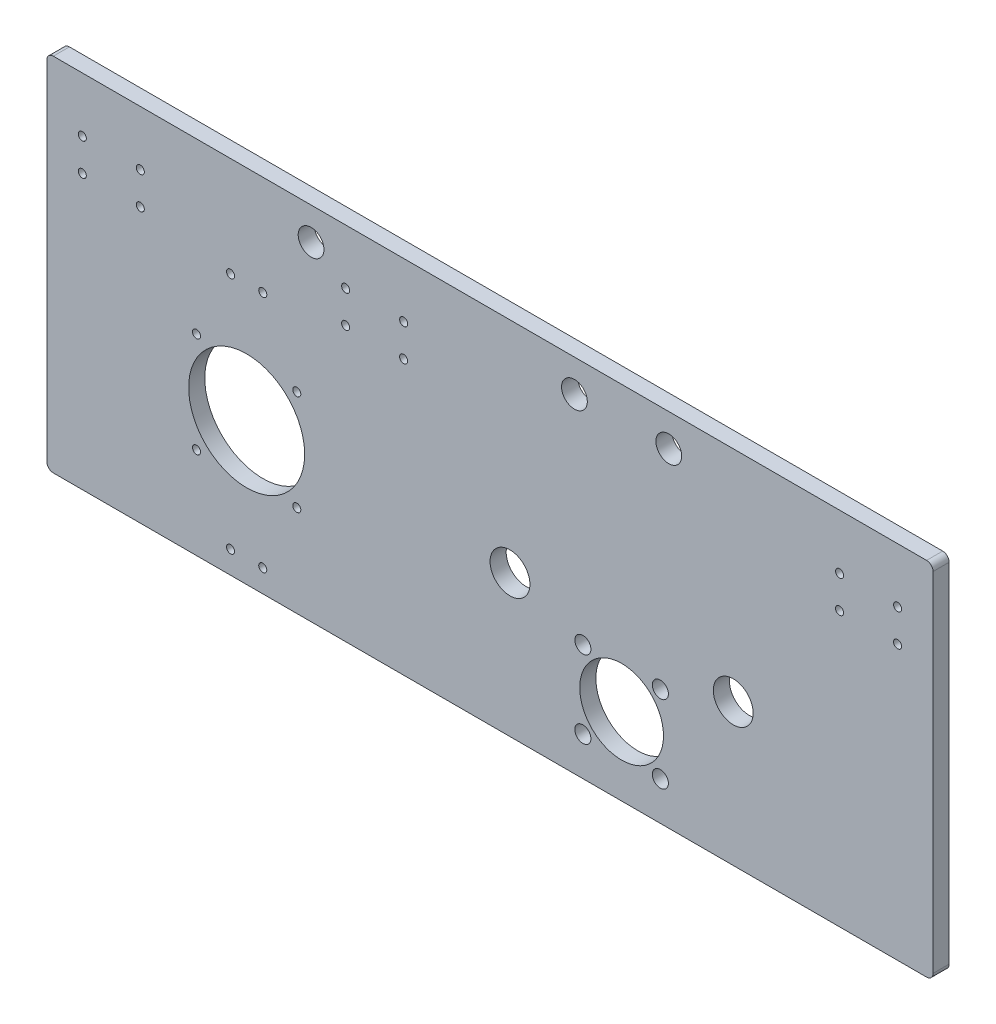
SolidWorks part; units mm, degrees
ref_plane "Спереди" through (0, 0, 0) normal (0, 0, 1) x (1, 0, 0)
ref_plane "Сверху" through (0, 0, 0) normal (0, 1, 0) x (1, 0, 0)
ref_plane "Справа" through (0, 0, 0) normal (1, 0, 0) x (0, 0, -1)
sketch "Эскиз1" plane through (0, 0, 0) normal (0, 0, 1) x (1, 0, 0)
  line L0 (-12.0208, 12.0208) -> (0, 0) construction
  line L1 (-178.359, 88) -> (96.641, 88)
  line L2 (-178.359, 88) -> (-178.359, -24)
  line L3 (-178.359, -24) -> (96.641, -24)
  line L4 (96.641, 88) -> (96.641, -24)
  line L5 (0, 0) -> (0, 88) construction
  line L6 (-34.641, 20) -> (0, 0) construction
  circle A0 centre (0, 0) radius 13
  circle A1 centre (-12.0208, 12.0208) radius 2.5
  circle A2 centre (12.0208, 12.0208) radius 2.5
  circle A3 centre (12.0208, -12.0208) radius 2.5
  circle A4 centre (-12.0208, -12.0208) radius 2.5
  circle A5 centre (-34.641, 20) radius 6.1833
  circle A6 centre (34.641, 20) radius 6.1833
  circle A7 centre (-116.359, 20) radius 18
  circle A8 centre (-14.641, 78) radius 4
  circle A9 centre (14.641, 78) radius 4
  circle A10 centre (-96.359, 78) radius 4
  circle A11 centre (-116.359, 20) radius 18 construction
  point P19 (0, 0)
  dimension "D2" = 5
  dimension "D4" = 26
  dimension "D9" = 8
  dimension "D1" = 45
  dimension "D3" = 17
  dimension "D6" = 58
  dimension "D7" = 20
  dimension "D8" = 20
  dimension "D10" = 10
  dimension "D12" = 40
  dimension "D13" = 20
  dimension "D14" = 275
  dimension "D15" = 82
  dimension "D16" = 82
  dimension "D11" = 112
  dimension "D5" = 4
extrude "Бобышка-Вытянуть1" add sketch "Эскиз1" along normal blind 5
hole_wizard "Отверстие обработанное метчиком M32" positions "Эскиз2" profile "Эскиз4" tap size "M3" standard "ISO" end condition through all
sketch "Эскиз2" plane through (0, 0, 0) normal (0, 0, -1) x (-1, 0, 0)
  point P0 (111.359, 57)
  point P3 (121.359, 57)
  point P6 (111.359, -17)
  point P9 (121.359, -17)
sketch "Эскиз4" plane through (-111.359, 57, 0) normal (1, 0, 0) x (0, 1, 0)
  line L0 (0, 0) -> (0, 5)
  line L1 (0, 5) -> (1.25, 5)
  line L2 (1.25, 5) -> (1.25, 0)
  line L5 (1.25, 0) -> (0, 0)
  line L11 (0, -6.35) -> (0, 107.95) construction
  dimension "Диаметр проходного сверла" = 2.5
  dimension "Глубина проходного сверла" = 5
cosmetic thread "Отверстие резьбы1" parameters "D2"=3
cosmetic thread "Отверстие резьбы2" parameters "D2"=3
cosmetic thread "Отверстие резьбы3" parameters "D2"=3
cosmetic thread "Отверстие резьбы4" parameters "D2"=3
hole_wizard "Отверстие обработанное метчиком M31" positions "Трехмерный эскиз1" profile "Эскиз6" tap size "M3" standard "ISO"
sketch3d "Трехмерный эскиз1"
  line L0 (-167.359, 71, 5) -> (-167.359, 71, 6) construction
  line L1 (-167.359, 61, 5) -> (-167.359, 61, 6) construction
  line L2 (-149.359, 61, 5) -> (-149.359, 61, 6) construction
  line L3 (-149.359, 71, 5) -> (-149.359, 71, 6) construction
  line L4 (-85.641, 71, 5) -> (-85.641, 71, 6) construction
  line L5 (-85.641, 61, 5) -> (-85.641, 61, 6) construction
  line L6 (-67.641, 61, 5) -> (-67.641, 61, 6) construction
  line L7 (-67.641, 71, 5) -> (-67.641, 71, 6) construction
  line L8 (67.641, 71, 5) -> (67.641, 71, 6) construction
  line L9 (67.641, 61, 5) -> (67.641, 61, 6) construction
  line L10 (85.641, 71, 5) -> (85.641, 71, 6) construction
  line L11 (85.641, 61, 5) -> (85.641, 61, 6) construction
  point P0 (-167.359, 71, 6)
  point P4 (-167.359, 61, 6)
  point P8 (-149.359, 61, 6)
  point P12 (-149.359, 71, 6)
  point P16 (-85.641, 71, 6)
  point P20 (-85.641, 61, 6)
  point P24 (-67.641, 61, 6)
  point P28 (-67.641, 71, 6)
  point P32 (67.641, 71, 6)
  point P36 (67.641, 61, 6)
  point P40 (85.641, 71, 6)
  point P44 (85.641, 61, 6)
sketch "Эскиз6" plane through (-167.359, 71, 6) normal (1, 0, 0) x (0, -1, 0)
  line L0 (0, 0) -> (0, 6.7501)
  line L1 (0, 6.7501) -> (1.25, 5.999)
  line L2 (1.25, 5.999) -> (1.25, 0)
  line L5 (1.25, 0) -> (0, 0)
  line L10 (0, 6.7501) -> (-1.25, 5.999) construction
  line L11 (0, -6.35) -> (0, 107.95) construction
  dimension "Диаметр сверла" = 2.5
  dimension "Глубина сверла" = 5.999
  dimension "Угол заточки сверла" = 118
cosmetic thread "Отверстие резьбы5" parameters "D1"=5, "D2"=3
cosmetic thread "Отверстие резьбы6" parameters "D1"=5, "D2"=3
cosmetic thread "Отверстие резьбы7" parameters "D1"=5, "D2"=3
cosmetic thread "Отверстие резьбы8" parameters "D1"=5, "D2"=3
cosmetic thread "Отверстие резьбы9" parameters "D1"=5, "D2"=3
cosmetic thread "Отверстие резьбы10" parameters "D1"=5, "D2"=3
cosmetic thread "Отверстие резьбы11" parameters "D1"=5, "D2"=3
cosmetic thread "Отверстие резьбы12" parameters "D1"=5, "D2"=3
cosmetic thread "Отверстие резьбы13" parameters "D1"=5, "D2"=3
cosmetic thread "Отверстие резьбы14" parameters "D1"=5, "D2"=3
cosmetic thread "Отверстие резьбы15" parameters "D1"=5, "D2"=3
cosmetic thread "Отверстие резьбы16" parameters "D1"=5, "D2"=3
sketch "Эскиз5" plane through (0, 0, 5) normal (0, 0, 1) x (1, 0, 0)
  line L0 (-178.359, 66) -> (96.641, 66)
  line L1 (-178.359, 88) -> (-178.359, -24) construction
  line L2 (96.641, -24) -> (96.641, 88) construction
  line L3 (-146.359, 78) -> (-146.359, -24)
  line L4 (-178.359, -24) -> (96.641, -24) construction
  line L5 (-64.641, 78) -> (-64.641, -24)
  line L6 (64.641, 78) -> (64.641, -24)
  circle A0 centre (14.641, 78) radius 4 construction
  circle A1 centre (14.641, 78) radius 4 construction
  circle A2 centre (14.641, 78) radius 50 construction
  circle A3 centre (-14.641, 78) radius 50 construction
  circle A4 centre (-96.359, 78) radius 50 construction
  dimension "D2" = 100
  dimension "D1" = 12
ref_plane "Плоскость1" through (0, 66, 0) normal (0, 1, 0) x (1, 0, 0)
ref_plane "Плоскость2" through (-146.359, 0, 0) normal (1, 0, 0) x (0, 0, -1)
ref_plane "Плоскость3" through (-64.641, 0, 0) normal (1, 0, 0) x (0, 0, -1)
ref_plane "Плоскость4" through (64.641, 0, 0) normal (1, 0, 0) x (0, 0, -1)
fillet "Скругление1" radius 2 4 edges at (-178.359, -24, 2.5) (96.641, -24, 2.5) (96.641, 88, 2.5) (-178.359, 88, 2.5)
hole_wizard "Отверстие обработанное метчиком M35" positions "Эскиз12" profile "Эскиз13" tap size "M3" standard "DIN" end condition up to next
sketch "Эскиз12" plane through (0, 0, 5) normal (0, 0, 1) x (1, 0, 0)
  point P0 (-100.8026, 35.5563)
sketch "Эскиз13" plane through (-100.8026, 35.5563, 5) normal (1, 0, 0) x (0, -1, 0)
  line L0 (0, 0) -> (0, 5)
  line L1 (0, 5) -> (1.25, 5)
  line L2 (1.25, 5) -> (1.25, 0)
  line L5 (1.25, 0) -> (0, 0)
  line L11 (0, -6.35) -> (0, 107.95) construction
  dimension "Диаметр проходного сверла" = 2.5
  dimension "Глубина проходного сверла" = 5
pattern_circular "Круговой массив1" count 4 over 360 about axis through (-116.359, 20, 0) along (0, 0, 1) of "Отверстие обработанное метчиком M35"
equation "\"Диаметр резьбы редуктора\" = 4  'Диаметр резьбы на фланце"
equation "\"Глубина резьбы редуктора\" = 7  'Диаметр резьбы на фланце"
equation "\"Диаметр окружности расположения редуктора\" = 34  'Диаметр расположения резьбы на фланце"
equation "\"Диаметр бурта редуктора\" = 26  'Диаметр бурта на фланце (Посадка h7)"
equation "\"Угл сдвига редуктора\" = 45"
equation "\"D1@Эскиз1\"=\"Угл сдвига редуктора\""
equation "\"D2@Эскиз1\"=\"Диаметр резьбы редуктора\"+1"
equation "\"D3@Эскиз1\"=\"Диаметр окружности расположения редуктора\"/2"
equation "\"D4@Эскиз1\"=\"Диаметр бурта редуктора\""
equation "\"Толщина пластины\" = 5"
equation "\"Межосевое прижима Вертикаль\" = 18  '!!!"
equation "\"Межосевое прижима Горизонталь\" = 20  '!!!"
equation "\"D7@Эскиз1\"=\"Межосевое прижима Горизонталь\""
equation "\"D8@Эскиз1\"=\"Межосевое прижима Горизонталь\""
equation "\"D1@Бобышка-Вытянуть1\"=\"Толщина пластины\""
equation "\"D6@Эскиз1\"=\"Межосевое прижима Вертикаль\"+\"Внешний диаметр ролика\""
equation "\"Внешний диаметр ролика\" = 40  'Внешний диаметр ролика"
equation "\"Диаметр вала ролика\" = 8  '!!!"
equation "\"D9@Эскиз1\"=\"Диаметр вала ролика\""
equation "\"D2@Эскиз5\"=28*2+44"
equation "\"D16@Эскиз1\"=\"D15@Эскиз1\""
